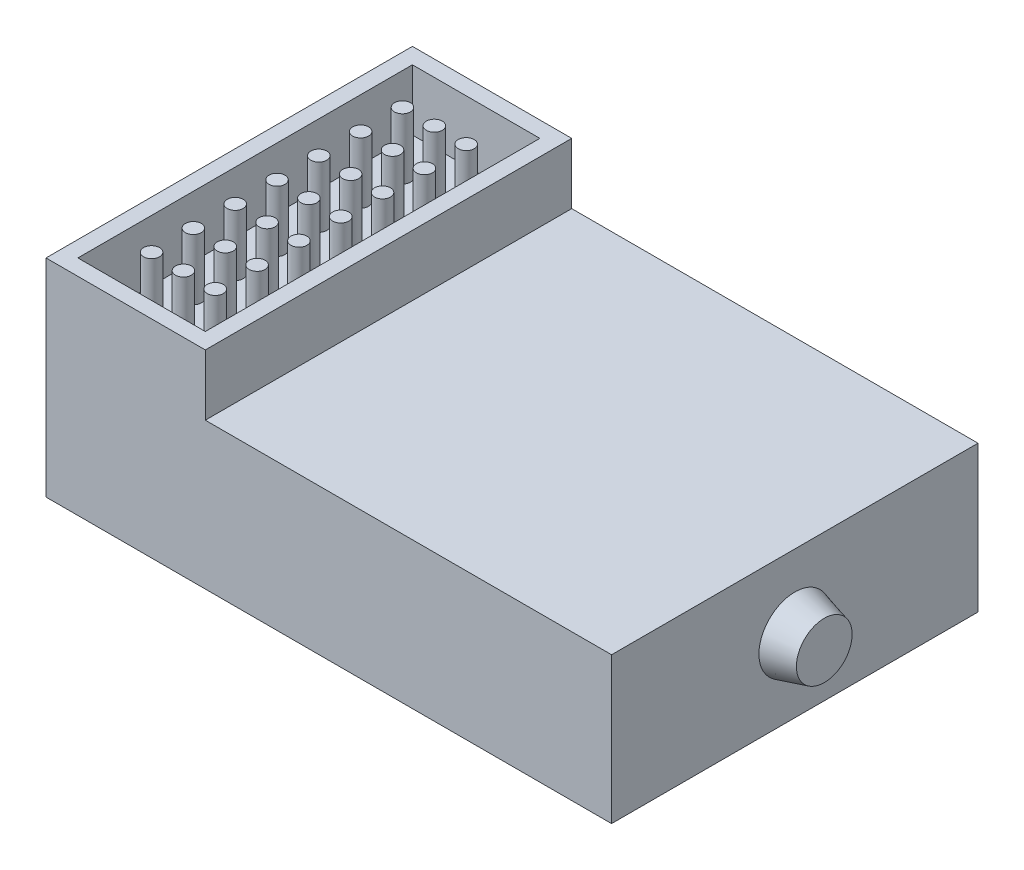
SolidWorks part; units mm, degrees
material "ABS PC"
ref_plane "Front Plane" through (0, 0, 0) normal (0, 0, 1) x (1, 0, 0)
ref_plane "Top Plane" through (0, 0, 0) normal (0, 1, 0) x (1, 0, 0)
ref_plane "Right Plane" through (0, 0, 0) normal (1, 0, 0) x (0, 0, -1)
sketch "Sketch1" plane through (0, 0, 0) normal (0, 1, 0) x (1, 0, 0)
  line L1 (-17.75, -11.5) -> (17.75, -11.5)
  line L2 (-17.75, -11.5) -> (-17.75, 11.5)
  line L3 (-17.75, 11.5) -> (17.75, 11.5)
  line L4 (17.75, -11.5) -> (17.75, 11.5)
  line L5 (-17.75, -11.5) -> (17.75, 11.5) construction
  line L6 (-17.75, 11.5) -> (17.75, -11.5) construction
  point P0 (0, 0)
  dimension "D1" = 35.5
  dimension "D2" = 23
extrude "Boss-Extrude1" add sketch "Sketch1" along normal blind 9.18
sketch "Sketch2" plane through (0, 9.18, 0) normal (0, 1, 0) x (1, 0, 0)
  line L0 (-17.75, -11.5) -> (17.75, -11.5) construction
  line L1 (-17.75, 11.5) -> (-7.75, 11.5)
  line L2 (-17.75, 11.5) -> (-17.75, -11.5)
  line L3 (-17.75, -11.5) -> (-7.75, -11.5)
  line L4 (-7.75, 11.5) -> (-7.75, -11.5)
  line L5 (-17.75, 11.5) -> (-7.75, -11.5) construction
  line L6 (-17.75, -11.5) -> (-7.75, 11.5) construction
  line L11 (-16.75, 10.5) -> (-16.75, -10.5)
  line L12 (-16.75, -10.5) -> (-8.75, -10.5)
  line L13 (-8.75, 10.5) -> (-8.75, -10.5)
  line L14 (-16.75, 10.5) -> (-8.75, 10.5)
  point P4 (-12.75, 0)
  dimension "D1" = 10
  dimension "D2" = 1
extrude "Boss-Extrude2" add sketch "Sketch2" along normal blind 3.82
sketch "Sketch3" plane through (0, 9.18, 0) normal (0, 1, 0) x (1, 0, 0)
  line L0 (-14.75, 7.875) -> (-16.75, 7.875) construction
  line L1 (-8.75, 10.5) -> (-16.75, 10.5) construction
  line L2 (-16.75, 10.5) -> (-16.75, -10.5) construction
  line L3 (-14.75, 7.875) -> (-14.75, 10.5) construction
  line L4 (-14.75, 7.875) -> (-14.75, 5.25) construction
  line L5 (-12.75, 7.875) -> (-14.75, 7.875) construction
  circle A0 centre (-14.75, 7.875) radius 0.5
  circle A1 centre (-12.75, 7.875) radius 0.5
  circle A2 centre (-10.75, 7.875) radius 0.5
  circle A3 centre (-12.75, 5.25) radius 0.5
  circle A4 centre (-10.75, 5.25) radius 0.5
  circle A5 centre (-12.75, 2.625) radius 0.5
  circle A6 centre (-10.75, 2.625) radius 0.5
  circle A7 centre (-12.75, 0) radius 0.5
  circle A8 centre (-10.75, 0) radius 0.5
  circle A9 centre (-12.75, -2.625) radius 0.5
  circle A10 centre (-10.75, -2.625) radius 0.5
  circle A11 centre (-12.75, -5.25) radius 0.5
  circle A12 centre (-10.75, -5.25) radius 0.5
  circle A13 centre (-12.75, -7.875) radius 0.5
  circle A14 centre (-10.75, -7.875) radius 0.5
  circle A15 centre (-14.75, 5.25) radius 0.5
  circle A16 centre (-14.75, 2.625) radius 0.5
  circle A17 centre (-14.75, 0) radius 0.5
  circle A18 centre (-14.75, -2.625) radius 0.5
  circle A19 centre (-14.75, -5.25) radius 0.5
  circle A20 centre (-14.75, -7.875) radius 0.5
  point P2 (-14.75, 7.875)
  dimension "D3" = 1
  dimension "D1" = 2.625
  dimension "D2" = 2
  dimension "D4" = 3
  dimension "D5" = 7
extrude "Boss-Extrude3" add sketch "Sketch3" along normal up to surface (3.82 mm away) up to face at (-12.75, 13, 0)
sketch "Sketch5" plane through (0, 0, 0) normal (0, 0, 1) x (1, 0, 0)
  line L0 (17.75, 9.18) -> (17.75, 0) construction
  line L1 (17.75, 9.18) -> (17.75, 0) construction
  line L2 (17.75, 4.59) -> (19.6, 4.59)
  line L3 (19.6, 4.59) -> (19.6, 6.34)
  line L4 (19.6, 6.34) -> (17.75, 6.84)
  line L5 (17.75, 6.84) -> (17.75, 4.59)
  dimension "D1" = 1.85
  dimension "D2" = 2.25
  dimension "D3" = 1.75
revolve "Revolve1" add sketch "Sketch5" angle 360 about L2
